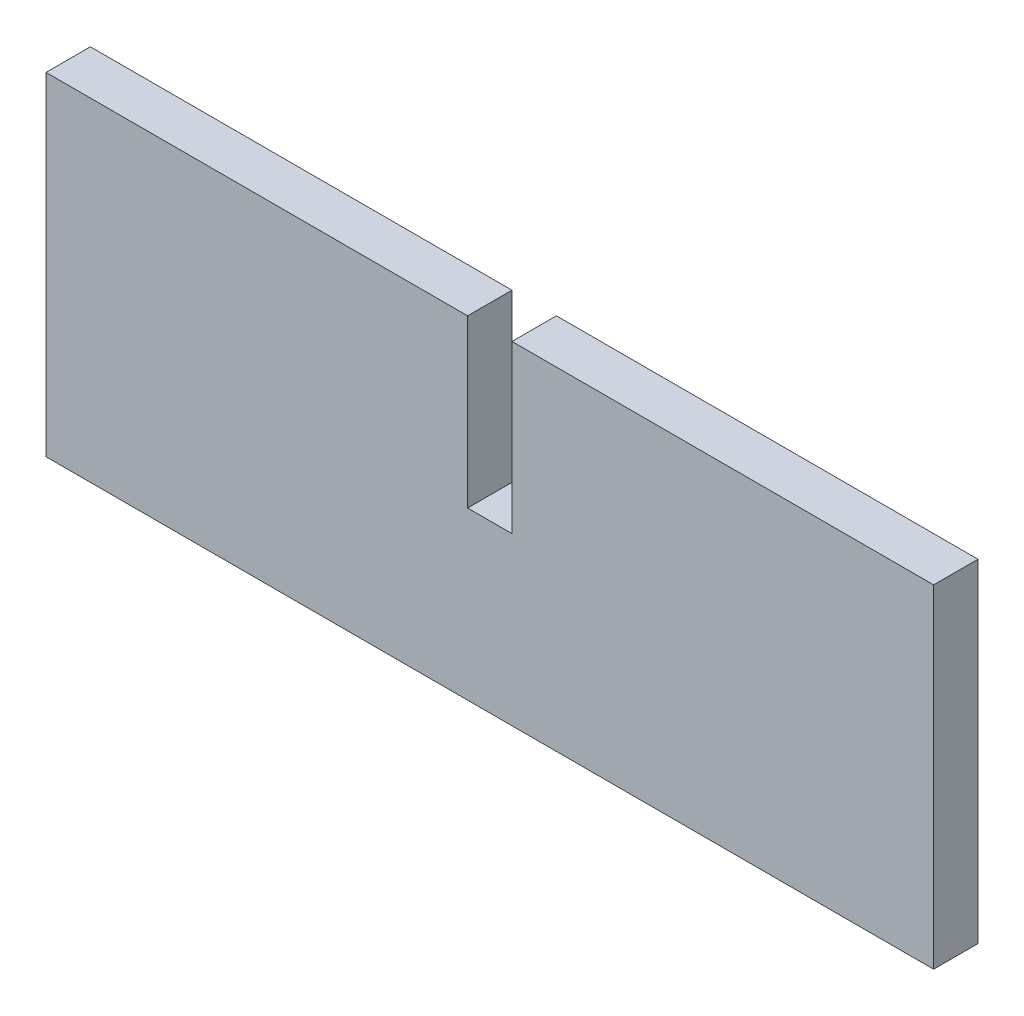
SolidWorks part; units mm, degrees
ref_plane "Plan de face" through (0, 0, 0) normal (0, 0, 1) x (1, 0, 0)
ref_plane "Plan de dessus" through (0, 0, 0) normal (0, 1, 0) x (1, 0, 0)
ref_plane "Plan de droite" through (0, 0, 0) normal (1, 0, 0) x (0, 0, -1)
sketch "Esquisse1" plane through (0, 0, 0) normal (0, 0, 1) x (1, 0, 0)
  line L0 (0, 0) -> (0, 60) construction
  line L1 (-4, 60) -> (-80, 60)
  line L2 (-80, 60) -> (-80, 0)
  line L3 (-80, 0) -> (80, 0)
  line L4 (-4, 60) -> (-4, 30)
  line L5 (-4, 30) -> (4, 30)
  line L6 (4, 60) -> (4, 30)
  line L7 (80, 60) -> (80, 0)
  line L8 (4, 60) -> (80, 60)
  point P9 (0, 30)
  dimension "D1" = 60
  dimension "D2" = 8
  dimension "D3" = 160
  dimension "D4" = 30
extrude "Boss.-Extru.1" add sketch "Esquisse1" along normal blind 8
